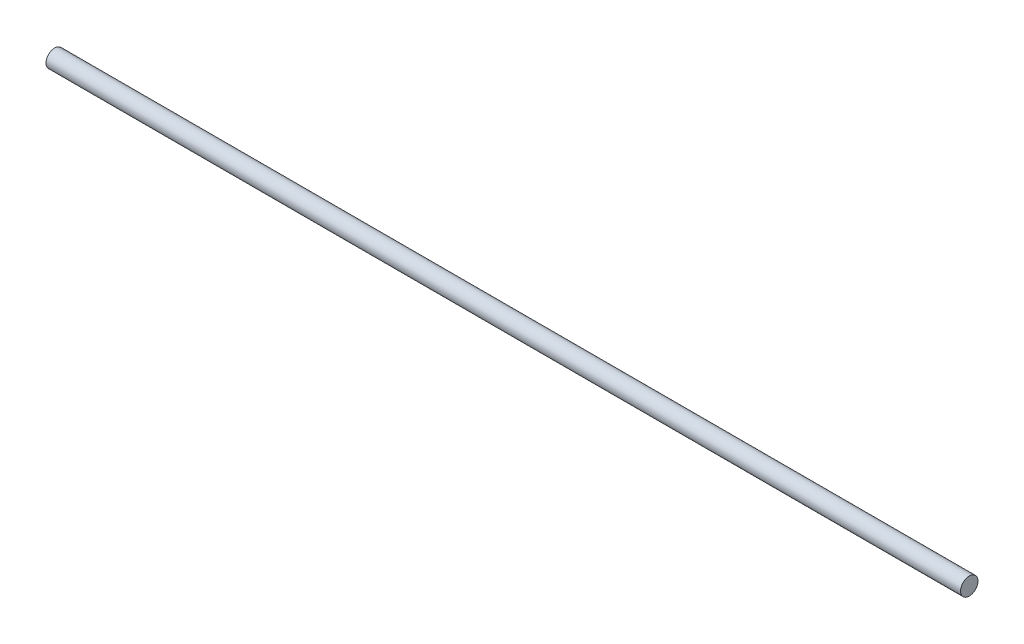
SolidWorks part; units mm, degrees
ref_plane "Plano frontal" through (0, 0, 0) normal (0, 0, 1) x (1, 0, 0)
ref_plane "Plano superior" through (0, 0, 0) normal (0, 1, 0) x (1, 0, 0)
ref_plane "Plano direito" through (0, 0, 0) normal (1, 0, 0) x (0, 0, -1)
sketch "Esboço1" plane through (0, 0, 0) normal (1, 0, 0) x (0, 0, -1)
  circle A0 centre (0, 0) radius 4
  dimension "D1" = 8
extrude "Ressalto-extrusão1" add sketch "Esboço1" along normal blind 420
